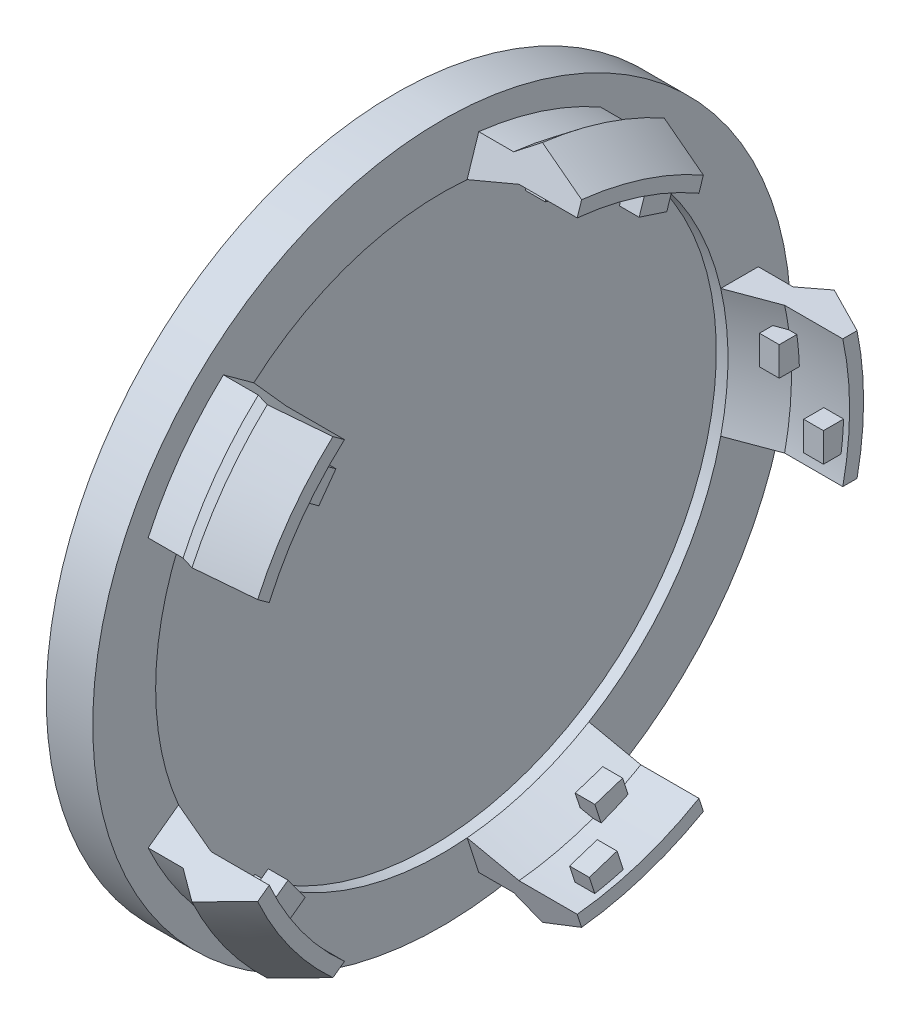
SolidWorks part; units mm, degrees
ref_plane "Спереди" through (0, 0, 0) normal (0, 0, 1) x (1, 0, 0)
ref_plane "Сверху" through (0, 0, 0) normal (0, 1, 0) x (1, 0, 0)
ref_plane "Справа" through (0, 0, 0) normal (1, 0, 0) x (0, 0, -1)
sketch "Эскиз1" plane through (0, 0, 0) normal (0, 0, 1) x (1, 0, 0)
  line L0 (0, 0) -> (-38.6181, 0) construction
  line L1 (0, 30) -> (4, 30)
  line L2 (4, 30) -> (4, 26)
  line L3 (4, 26) -> (3, 26)
  line L4 (3, 26) -> (3, 0)
  line L7 (0, 0) -> (3, 0)
  line L8 (0, 30) -> (0, 0)
  dimension "D1" = 60
  dimension "D2" = 52
  dimension "D3" = 4
  dimension "D7" = 1
revolve "Повернуть1" add sketch "Эскиз1" angle 360 about L0
sketch "Эскиз2" plane through (0, 0, 0) normal (0, 0, 1) x (1, 0, 0)
  line L0 (0, 0) -> (4, 0) construction
  line L1 (4, 0) -> (4, 24.5941) construction
  line L2 (4, 24.5941) -> (8, 26.05)
  line L3 (8, 26.05) -> (13, 26.05)
  line L4 (13, 26.05) -> (13, 27.25)
  line L5 (13, 27.25) -> (9, 29.25)
  line L6 (9, 29.25) -> (7, 27.75)
  line L7 (7, 27.75) -> (3, 27.75)
  line L8 (3, 27.75) -> (3, 24.5941)
  line L9 (3, 24.5941) -> (4, 24.5941)
  line L10 (3, -26) -> (3, 26) construction
  dimension "D1" = 58.5
  dimension "D2" = 2
  dimension "D3" = 1.2
  dimension "D4" = 1.5
  dimension "D5" = 2
  dimension "D6" = 4
  dimension "D7" = 9
  dimension "D8" = 5
  dimension "D9" = 1
  dimension "D10" = 20
revolve "Повернуть2" add sketch "Эскиз2" angle 360 about L0
sketch "Эскиз3" plane through (13, 0, 0) normal (1, 0, 0) x (0, 0, -1)
  line L0 (0, 0) -> (22.1101, 0) construction
  line L1 (31.7273, 5.5) -> (23.9712, 5.5)
  line L2 (31.7273, -5.5) -> (23.9712, -5.5)
  line L3 (15.0351, -28.4749) -> (12.6383, -21.0984)
  line L4 (4.5735, -31.8741) -> (2.1767, -24.4976)
  line L5 (-22.4351, -23.0984) -> (-16.1603, -18.5395)
  line L6 (-28.9008, -14.1993) -> (-22.626, -9.6404)
  line L7 (-28.9008, 14.1993) -> (-22.626, 9.6404)
  line L8 (-22.4351, 23.0984) -> (-16.1603, 18.5395)
  line L9 (4.5735, 31.8741) -> (2.1767, 24.4976)
  line L10 (15.0351, 28.4749) -> (12.6383, 21.0984)
  circle A0 centre (0, 0) radius 24.5941
  circle A1 centre (0, 0) radius 32.2005
  circle A2 centre (0, 0) radius 24.5941 construction
  point P28 (0, 0)
  circle M5 centre (0, 0) radius 27.25
  circle M6 centre (0, 0) radius 26.05
  dimension "D1" = 11
  dimension "D2" = 5
extrude "Вырез-Вытянуть1" cut sketch "Эскиз3" against normal blind 9 contours L3 L2 M5 M6 | A0 L3 L2 M6 | L5 L4 M5 M6 | A0 L5 L4 M6 | L7 L6 M5 M6 | A0 L7 L6 M6 | L9 L8 M5 M6 | A0 L9 L8 M6 | L10 L1 M5 M6 | A0 L1 L10 M6 | L9 A1 L8 M5 | L7 A1 L6 M5 | L5 A1 L4 M5 | L3 A1 L2 M5 | L1 A1 L10 M5
ref_plane "Плоскость1" through (0, 0, -24.3) normal (0, 0, 1) x (1, 0, 0)
sketch "Эскиз4" plane through (0, 0, -24.3) normal (0, 0, 1) x (1, 0, 0)
  line L0 (13, -5.5) -> (13, 5.5) construction
  line L1 (12.5, -1) -> (10.8, -1)
  line L2 (12.5, -1) -> (12.5, -3.5)
  line L3 (12.5, -3.5) -> (10.8, -3.5)
  line L4 (10.8, -1) -> (10.8, -3.5)
  line L5 (12.5, -1) -> (10.8, -3.5) construction
  line L6 (12.5, -3.5) -> (10.8, -1) construction
  line L7 (8.7, 3.5) -> (7, 3.5)
  line L8 (8.7, 3.5) -> (8.7, 1)
  line L9 (8.7, 1) -> (7, 1)
  line L10 (7, 3.5) -> (7, 1)
  line L11 (8.7, 3.5) -> (7, 1) construction
  line L12 (8.7, 1) -> (7, 3.5) construction
  line L13 (8, -5.5) -> (13, -5.5) construction
  line L14 (8, 5.5) -> (13, 5.5) construction
  point P0 (11.65, -2.25)
  point P5 (7.85, 2.25)
  dimension "D1" = 2.5
  dimension "D2" = 2.5
  dimension "D3" = 1.7
  dimension "D4" = 1.7
  dimension "D5" = 0.5
  dimension "D6" = 2
  dimension "D7" = 4.3
  dimension "D8" = 2
  dimension "D9" = 2.1
extrude "Бобышка-Вытянуть1" add sketch "Эскиз4" against normal blind 2
pattern_circular "Круговой массив1" count 5 over 360 about axis through (0, 0, 0) along (1, 0, 0) of "Бобышка-Вытянуть1"
ref_plane "Плоскость2" through (-37.3357, 0, 0) normal (1, 0, 0) x (0, 0, -1)
sketch "Эскиз5" plane through (0, 0, 0) normal (1, 0, 0) x (0, 0, -1)
  line L0 (0, 0) -> (0, 19.5)
  line L1 (5.5, 18.7083) -> (0, 6.1217) construction
  line L2 (10.0766, 16.6947) -> (3, 0.5) construction
  line L3 (3, 0.5) -> (-3, 0.5) construction
  line L4 (0, 0) -> (-19.5, 0)
  line L5 (-5.5, 18.7083) -> (0, 6.1217) construction
  line L6 (-10.0766, 16.6947) -> (-3, 0.5) construction
  line L7 (0, 0) -> (0, -30)
  line L8 (-3, -0.5) -> (3, -0.5) construction
  line L9 (3, 0.5) -> (3, -0.5)
  line L10 (3, -0.5) -> (7, -8.0165) construction
  line L11 (7, -8.0165) -> (15.5, 11.8322) construction
  line L12 (0, -6.5) -> (5.5, -18.7083) construction
  line L13 (8.3046, -17.6432) -> (18.5, 6.1644) construction
  line L14 (0, -6.5) -> (-5.5, -18.7083) construction
  line L15 (-8.3046, -17.6432) -> (-18.5, 6.1644) construction
  line L16 (-7, -8.0165) -> (-15.5, 11.8322) construction
  line L17 (-3, -0.5) -> (-7, -8.0165) construction
  line L18 (-5.0876, 18.5137) -> (0, 6.8709)
  line L19 (5.0876, 18.5137) -> (0, 6.8709)
  line L20 (-10.2133, 16.2582) -> (-3.1963, 0.2)
  line L21 (3.1963, 0.2) -> (-3.1963, 0.2)
  line L22 (10.2133, 16.2582) -> (3.1963, 0.2)
  line L23 (6.9707, -7.3228) -> (15.1549, 11.7885)
  line L24 (3.1802, -0.2) -> (6.9707, -7.3228)
  line L25 (-3.1802, -0.2) -> (3.1802, -0.2)
  line L26 (-3.1802, -0.2) -> (-6.9707, -7.3228)
  line L27 (-6.9707, -7.3228) -> (-15.1549, 11.7885)
  line L28 (-8.9013, -17.012) -> (-18.4549, 5.297)
  line L29 (0, -7.2304) -> (-5.0838, -18.5147)
  line L30 (0, -7.2304) -> (5.0838, -18.5147)
  line L31 (8.9013, -17.012) -> (18.4549, 5.297)
  circle A0 centre (0, 0) radius 24 construction
  arc A1 (5.5, 18.7083) -> (-5.5, 18.7083) centre (0, 0) ccw construction
  arc A2 (-10.0766, 16.6947) -> (-15.5, 11.8322) centre (0, 0) ccw construction
  circle A3 centre (0, 0) radius 30 construction
  arc A4 (15.5, 11.8322) -> (10.0766, 16.6947) centre (0, 0) ccw construction
  arc A5 (-18.5, 6.1644) -> (-8.3046, -17.6432) centre (0, 0) ccw construction
  arc A6 (8.3046, -17.6432) -> (18.5, 6.1644) centre (0, 0) ccw construction
  arc A7 (-5.5, -18.7083) -> (5.5, -18.7083) centre (0, 0) ccw construction
  arc A9 (5.0876, 18.5137) -> (-5.0876, 18.5137) centre (0, 0) ccw
  arc A10 (15.1549, 11.7885) -> (10.2133, 16.2582) centre (0, 0) ccw
  circle A14 centre (0, 0) radius 24.3
  arc A15 (-10.2133, 16.2582) -> (-15.1549, 11.7885) centre (0, 0) ccw
  arc A16 (-18.4549, 5.297) -> (-8.9013, -17.012) centre (0, 0) ccw
  arc A17 (-5.0838, -18.5147) -> (5.0838, -18.5147) centre (0, 0) ccw
  arc A18 (8.9013, -17.012) -> (18.4549, 5.297) centre (0, 0) ccw
  point P12 (0, 0.5)
  point P30 (0, -0.5)
  dimension "D1" = 48
  dimension "D2" = 39
  dimension "D3" = 0.5
  dimension "D4" = 5
  dimension "D5" = 3
  dimension "D6" = 5.5
  dimension "D7" = 0.5
  dimension "D8" = 7
  dimension "D9" = 3
  dimension "D10" = 5.5
  dimension "D11" = 6
  dimension "D12" = 15.5
  dimension "D13" = 18.5
  dimension "D14" = 0.3
  dimension "D15" = 0.3
  dimension "D16" = 0.3
  dimension "D17" = 0.3
  dimension "D18" = 0.3
  dimension "D19" = 0.3
fillet "Скругление1" [suppressed] radius 1
extrude "Вырез-Вытянуть2" cut sketch "Эскиз5" along normal blind 1.5
